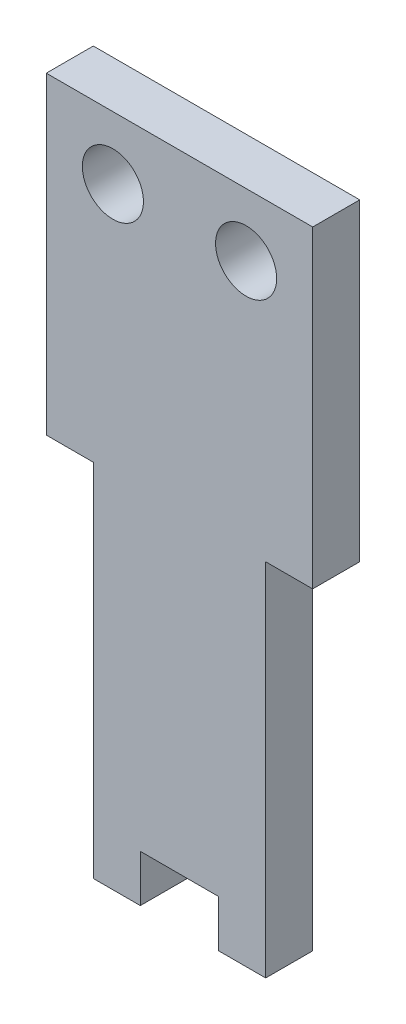
SolidWorks part; units mm, degrees
ref_plane "Front Plane" through (0, 0, 0) normal (0, 0, 1) x (1, 0, 0)
ref_plane "Top Plane" through (0, 0, 0) normal (0, 1, 0) x (1, 0, 0)
ref_plane "Right Plane" through (0, 0, 0) normal (1, 0, 0) x (0, 0, -1)
sketch "Sketch1" plane through (0, 0, 0) normal (0, 0, 1) x (1, 0, 0)
  line L0 (-8.5, -20) -> (-5.5, -20) construction
  line L1 (8.5, -20) -> (5.5, -20)
  line L2 (8.5, -20) -> (8.5, 20)
  line L3 (8.5, 20) -> (-8.5, 20)
  line L4 (-8.5, -20) -> (-8.5, 20)
  line L5 (8.5, -20) -> (-8.5, 20) construction
  line L6 (8.5, 20) -> (-8.5, -20) construction
  line L7 (0, -15) -> (0, -17.5152) construction
  line L9 (-5.5, -20) -> (-5.5, -23)
  line L10 (-5.5, -23) -> (-2.5, -23)
  line L11 (-2.5, -20) -> (-2.5, -23)
  line L12 (-5.5, -20) -> (-2.5, -23) construction
  line L13 (-5.5, -23) -> (-2.5, -20) construction
  line L14 (5.5, -23) -> (2.5, -23)
  line L15 (5.5, -20) -> (5.5, -23)
  line L16 (2.5, -20) -> (2.5, -23)
  line L17 (-5.5, -20) -> (-8.5, -20)
  line L18 (2.5, -20) -> (-2.5, -20)
  point P0 (0, 0)
  point P10 (-4, -21.5)
  dimension "D1" = 17
  dimension "D2" = 40
  dimension "D3" = 3
  dimension "D4" = 3
  dimension "D5" = 3
extrude "Boss-Extrude1" add sketch "Sketch1" along normal blind 3
sketch "Sketch2" plane through (0, 0, 3) normal (0, 0, 1) x (1, 0, 0)
  line L0 (-8.5, 16) -> (0, 16) construction
  line L1 (-8.5, 20) -> (-8.5, -20) construction
  line L2 (0, 16) -> (8.5, 16) construction
  line L3 (8.5, -20) -> (8.5, 20) construction
  line L4 (8.5, 20) -> (-8.5, 20) construction
  circle A0 centre (-4.25, 16) radius 1.95
  circle A1 centre (4.25, 16) radius 1.95
  dimension "D3" = 3.9
  dimension "D4" = 3.9
  dimension "D1" = 8.5
  dimension "D2" = 4
extrude "Cut-Extrude1" cut sketch "Sketch2" against normal through all
sketch "Sketch3" plane through (0, 0, 3) normal (0, 0, 1) x (1, 0, 0)
  line L1 (-8.5, -20) -> (-5.5, -20)
  line L2 (-8.5, -20) -> (-8.5, -16)
  line L3 (-8.5, -16) -> (-5.5, -16)
  line L4 (-5.5, -20) -> (-5.5, -16)
  line L5 (-8.5, -20) -> (-5.5, -16) construction
  line L6 (-8.5, -16) -> (-5.5, -20) construction
  line L7 (8.5, -20) -> (5.5, -20)
  line L8 (8.5, -20) -> (8.5, -16)
  line L9 (8.5, -16) -> (5.5, -16)
  line L10 (5.5, -20) -> (5.5, -16)
  line L11 (8.5, -20) -> (5.5, -16) construction
  line L12 (8.5, -16) -> (5.5, -20) construction
  point P4 (-7, -18)
  point P10 (7, -18)
  dimension "D1" = 4
  dimension "D2" = 3
  dimension "D3" = 3
extrude "Cut-Extrude2" cut sketch "Sketch3" against normal through all
sketch "Sketch4" plane through (0, 0, 3) normal (0, 0, 1) x (1, 0, 0)
  line L0 (-8.5, 20) -> (-8.5, -16) construction
  line L1 (-8.5, 0) -> (-5.5, 0)
  line L2 (-8.5, 0) -> (-8.5, -16)
  line L3 (-8.5, -16) -> (-5.5, -16)
  line L4 (-5.5, 0) -> (-5.5, -16)
  line L5 (-8.5, 0) -> (-5.5, -16) construction
  line L6 (-8.5, -16) -> (-5.5, 0) construction
  line L7 (8.5, -16) -> (8.5, 20) construction
  line L8 (5.5, -16) -> (8.5, -16)
  line L9 (5.5, -16) -> (5.5, 0)
  line L10 (5.5, 0) -> (8.5, 0)
  line L11 (8.5, -16) -> (8.5, 0)
  line L12 (5.5, -16) -> (8.5, 0) construction
  line L13 (5.5, 0) -> (8.5, -16) construction
  point P4 (-7, -8)
  point P12 (7, -8)
  dimension "D1" = 16
extrude "Cut-Extrude3" cut sketch "Sketch4" against normal blind 10
